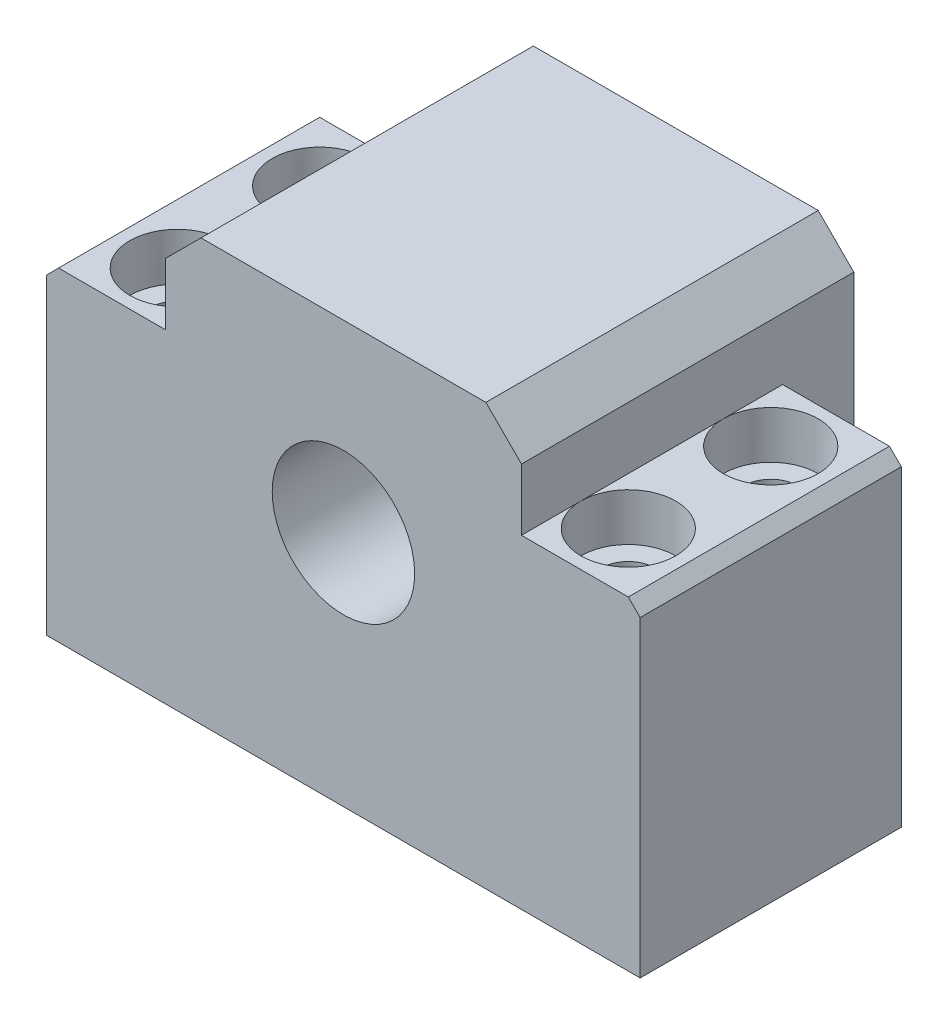
SolidWorks part; units mm, degrees
ref_plane "정면" through (0, 0, 0) normal (0, 0, 1) x (1, 0, 0)
ref_plane "윗면" through (0, 0, 0) normal (0, 1, 0) x (1, 0, 0)
ref_plane "우측면" through (0, 0, 0) normal (1, 0, 0) x (0, 0, -1)
sketch "스케치1" plane through (0, 0, 0) normal (0, 0, 1) x (1, 0, 0)
  line L1 (0, 0) -> (50, 0)
  line L2 (0, 0) -> (0, 27.3)
  line L3 (0, 27.3) -> (50, 27.3)
  line L4 (50, 0) -> (50, 27.3)
  dimension "D1" = 50
  dimension "D2" = 27.3
extrude "보스-돌출1" add sketch "스케치1" along normal blind 22
sketch "스케치2" plane through (0, 0, 22) normal (0, 0, 1) x (1, 0, 0)
  line L0 (25, 27.3) -> (25, 35.5) construction
  line L1 (10, 5.5) -> (40, 5.5)
  line L2 (10, 5.5) -> (10, 35.5)
  line L3 (10, 35.5) -> (40, 35.5)
  line L4 (40, 5.5) -> (40, 35.5)
  line L5 (50, 27.3) -> (0, 27.3) construction
  line L7 (0, 0) -> (50, 0) construction
  dimension "D1" = 30
  dimension "D2" = 30
  dimension "D3" = 5.5
extrude "보스-돌출2" add sketch "스케치2" against normal blind 28
sketch "스케치3" plane through (0, 0, -6) normal (0, 0, -1) x (-1, 0, 0)
  line L0 (0, 0) -> (-50, 0) construction
  circle A0 centre (-25, 20) radius 6
  dimension "D2" = 12
  dimension "D1" = 20
extrude "컷-돌출1" cut sketch "스케치3" against normal through all
chamfer "모따기1" distance 3 angle 45 2 edges at (10, 35.5, 8) (40, 35.5, 8)
chamfer "모따기2" distance 1 angle 45 2 edges at (0, 27.3, 11) (50, 27.3, 11)
sketch "스케치4" plane through (0, 27.3, 0) normal (0, -1, 0) x (1, 0, 0)
  line L1 (6, 5) -> (44, 5)
  line L2 (6, 5) -> (6, 17)
  line L3 (6, 17) -> (44, 17)
  line L4 (44, 5) -> (44, 17)
  line L5 (6, 5) -> (44, 17) construction
  line L6 (6, 17) -> (44, 5) construction
  line L7 (0, 22) -> (50, 22) construction
  line L8 (50, 22) -> (50, 0) construction
  point P0 (25, 11)
  dimension "D1" = 12
  dimension "D2" = 38
  dimension "D3" = 5
  dimension "D4" = 6
hole_wizard "M4 소켓 머리 캡 나사용 카운터보어1" positions "스케치6" profile "스케치5" counterbore size "M4" standard "KS" end condition through all
sketch "스케치6" plane through (0, 27.3, 0) normal (0, 1, 0) x (1, 0, 0)
  line L1 (6, -5) -> (44, -5)
  line L2 (6, -5) -> (6, -17)
  line L3 (6, -17) -> (44, -17)
  line L4 (44, -5) -> (44, -17)
  point P0 (44, -5)
  point P3 (44, -17)
  point P6 (6, -17)
  point P9 (6, -5)
  dimension "D1" = 38
  dimension "D2" = 12
sketch "스케치5" plane through (44, 27.3, 5) normal (1, 0, 0) x (0, 0, 1)
  line L0 (0, 0) -> (0, 27.3)
  line L1 (0, 27.3) -> (2.25, 27.3)
  line L3 (2.25, 27.3) -> (2.25, 4)
  line L4 (2.25, 4) -> (4, 4)
  line L5 (4, 4) -> (4, 0)
  line L7 (4, 0) -> (0, 0)
  line L11 (0, -6.35) -> (0, 107.95) construction
  dimension "관통 구멍 지름" = 4.5
  dimension "관통 구멍 깊이" = 27.3
  dimension "카운터보어 지름" = 8
  dimension "카운터보어 깊이" = 4
